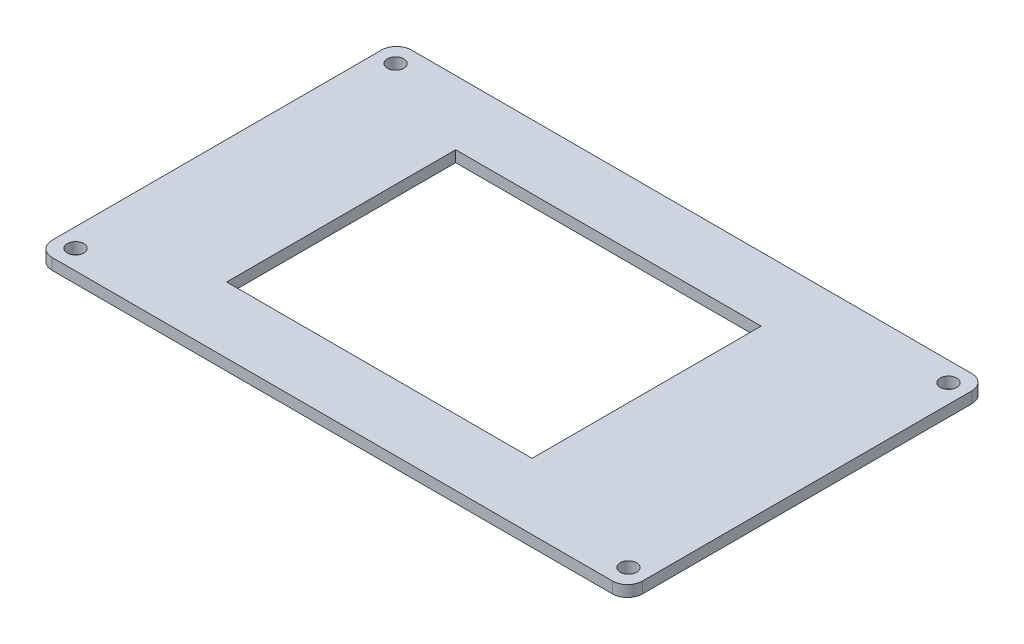
SolidWorks part; units mm, degrees
ref_plane "Front Plane" through (0, 0, 0) normal (0, 0, 1) x (1, 0, 0)
ref_plane "Top Plane" through (0, 0, 0) normal (0, 1, 0) x (1, 0, 0)
ref_plane "Right Plane" through (0, 0, 0) normal (1, 0, 0) x (0, 0, -1)
sketch "Sketch1" plane through (0, 0, 0) normal (0, 1, 0) x (1, 0, 0)
  line L1 (39.43, -24) -> (-39.43, -24)
  line L2 (39.43, -24) -> (39.43, 24)
  line L3 (39.43, 24) -> (-39.43, 24)
  line L4 (-39.43, -24) -> (-39.43, 24)
  line L5 (39.43, -24) -> (-39.43, 24) construction
  line L6 (39.43, 24) -> (-39.43, -24) construction
  line L11 (-22.94, 15.42) -> (17.86, 15.42)
  line L12 (-22.94, 15.42) -> (-22.94, -15.18)
  line L13 (-22.94, -15.18) -> (17.86, -15.18)
  line L14 (17.86, 15.42) -> (17.86, -15.18)
  point P0 (0, 0)
  point P6 (0, 0)
  dimension "D1" = 40.8
  dimension "D2" = 30.6
  dimension "D3" = 16.49
  dimension "D4" = 8.82
  dimension "D5" = 78.86
  dimension "D6" = 48
extrude "Boss-Extrude1" add sketch "Sketch1" along normal blind 1.5
sketch "Sketch2" plane through (0, 1.5, 0) normal (0, 1, 0) x (1, 0, 0)
  line L1 (36.93, -21.375) -> (-36.93, -21.375) construction
  line L2 (36.93, -21.375) -> (36.93, 21.375) construction
  line L3 (36.93, 21.375) -> (-36.93, 21.375) construction
  line L4 (-36.93, -21.375) -> (-36.93, 21.375) construction
  line L5 (36.93, -21.375) -> (-36.93, 21.375) construction
  line L6 (36.93, 21.375) -> (-36.93, -21.375) construction
  circle A0 centre (-36.93, 21.375) radius 1.1
  circle A1 centre (-36.93, -21.375) radius 1.1
  circle A2 centre (36.93, 21.375) radius 1.1
  circle A3 centre (36.93, -21.375) radius 1.1
  point P0 (0, 0)
  dimension "D3" = 2.2
  dimension "D1" = 73.86
  dimension "D2" = 42.75
extrude "Cut-Extrude1" cut sketch "Sketch2" against normal up to next
fillet "Fillet1" radius 2 4 edges at (-39.43, 0.75, -24) (39.43, 0.75, -24) (39.43, 0.75, 24) (-39.43, 0.75, 24)
